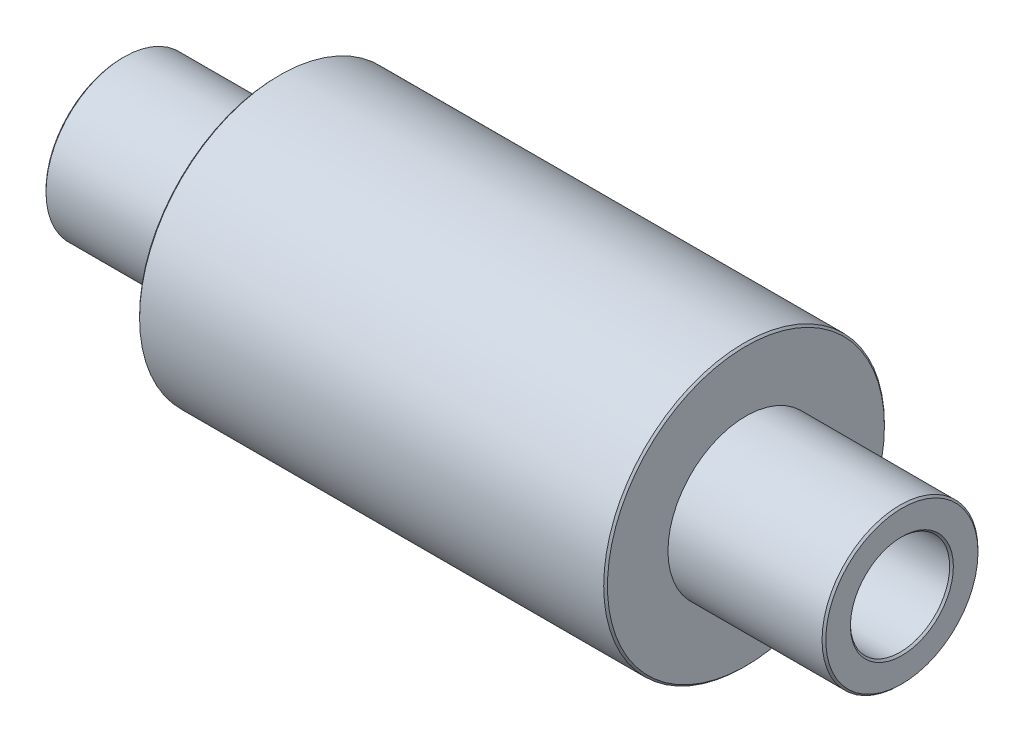
SolidWorks part; units mm, degrees
material "6061 Alloy"
ref_plane "Front Plane" through (0, 0, 0) normal (0, 0, 1) x (1, 0, 0)
ref_plane "Top Plane" through (0, 0, 0) normal (0, 1, 0) x (1, 0, 0)
ref_plane "Right Plane" through (0, 0, 0) normal (1, 0, 0) x (0, 0, -1)
sketch "Sketch34" plane through (0, 0, 0) normal (1, 0, 0) x (0, 0, -1)
  circle A0 centre (0, 0) radius 5.715
  dimension "D1" = 11.43
extrude "Boss-Extrude2" add sketch "Sketch34" along normal mid plane 31.75
hole_wizard "#21 (0.159) Diameter Hole2" positions "Sketch35" profile "Sketch36" hole size "#21" standard "ANSI Inch" end condition through all
sketch "Sketch35" plane through (15.875, 0, 0) normal (1, 0, 0) x (0, 0, -1)
  point P0 (0, 0)
sketch "Sketch36" plane through (15.875, 0, 0) normal (0, 1, 0) x (0, 0, -1)
  line L0 (0, 0) -> (0, 31.75)
  line L1 (0, 31.75) -> (2.0193, 31.75)
  line L2 (2.0193, 31.75) -> (2.0193, 0)
  line L5 (2.0193, 0) -> (0, 0)
  line L11 (0, -6.35) -> (0, 107.95) construction
  dimension "Thru Hole Dia." = 4.0386
  dimension "Thru Hole Depth" = 31.75
sketch "Sketch39" plane through (0, 0, 0) normal (0, 0, 1) x (1, 0, 0)
  line L0 (0, 0) -> (15.875, 0) construction
  line L1 (15.875, 5.715) -> (9.525, 5.715)
  line L2 (15.875, 5.715) -> (15.875, 3.175)
  line L3 (15.875, 3.175) -> (9.525, 3.175)
  line L4 (9.525, 5.715) -> (9.525, 3.175)
  line L5 (15.875, -5.715) -> (15.875, 5.715) construction
  dimension "D1" = 6.35
  dimension "D2" = 2.54
revolve "Cut-Revolve1" cut sketch "Sketch39" angle 360 about L0
chamfer "Chamfer1" distance 0.0762 angle 45 2 edges at (15.875, 0, 3.175) (9.525, 0, 5.715)
mirror "Mirror1" about plane through (0, 0, 0) normal (1, 0, 0) of "Cut-Revolve1"
chamfer "Chamfer2" distance 0.0762 angle 45 2 edges at (-15.875, 0, 3.175) (-9.525, 0, 5.715)
chamfer "Chamfer8" distance 0.0762 angle 45 2 edges at (-15.875, 0, -2.0193) (15.875, 0, -2.0193)
